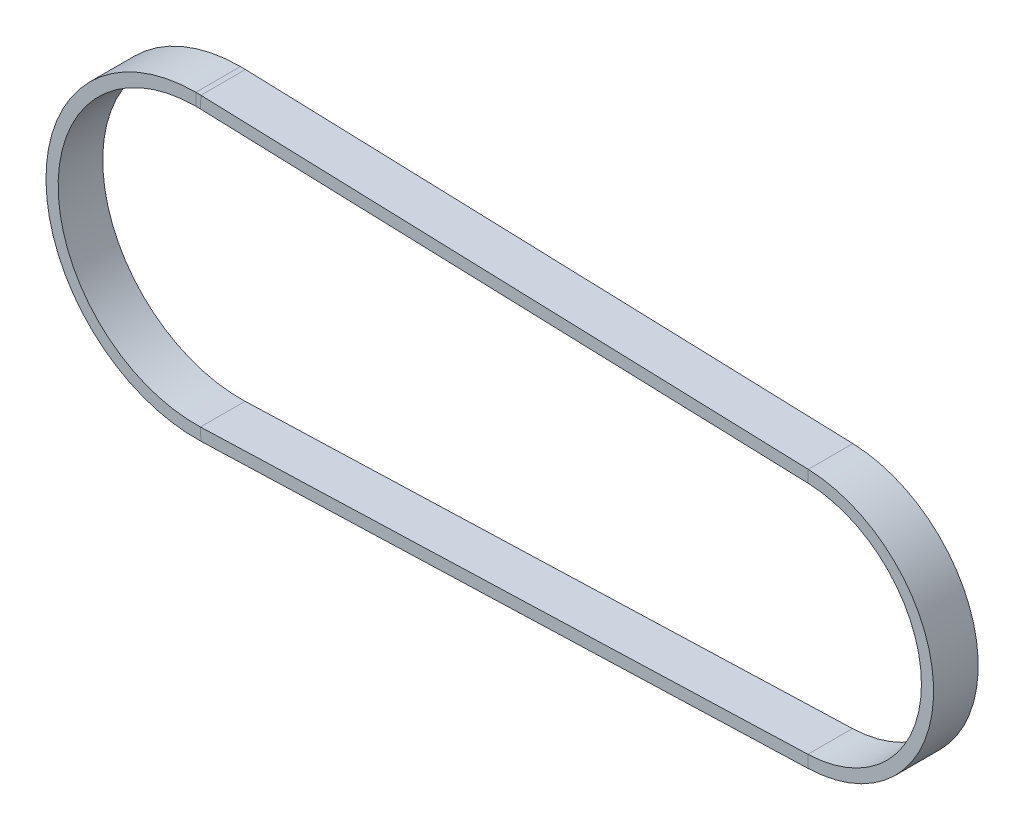
SolidWorks part; units mm, degrees
material "Rubber"
ref_plane "Front Plane" through (0, 0, 0) normal (0, 0, 1) x (1, 0, 0)
ref_plane "Top Plane" through (0, 0, 0) normal (0, 1, 0) x (1, 0, 0)
ref_plane "Right Plane" through (0, 0, 0) normal (1, 0, 0) x (0, 0, -1)
sketch "Sketch1" plane through (0, 0, 0) normal (0, 0, 1) x (1, 0, 0)
  line L0 (1.2333, 36.9794) -> (151.0667, 31.9822)
  line L1 (0, 0) -> (150, 0) construction
  line L2 (1.2333, -36.9794) -> (151.0667, -31.9822)
  arc A0 (1.2333, 36.9794) -> (1.2333, -36.9794) centre (0, 0) ccw
  arc A1 (151.0667, -31.9822) -> (151.0667, 31.9822) centre (150, 0) ccw
  dimension "D1" = 74
  dimension "D2" = 64
  dimension "D3" = 150
sketch "Sketch2" plane through (0, 0, 0) normal (1, 0, 0) x (0, 0, -1)
  line L0 (-5.5, 36.9794) -> (5.5, 36.9794)
  line L2 (-5.5, 36.9794) -> (-5.5, 33.9794)
  line L3 (-5.5, 33.9794) -> (5.5, 33.9794)
  line L4 (5.5, 33.9794) -> (5.5, 36.9794)
  point P3 (0, 36.9794)
  dimension "D1" = 11
  dimension "D2" = 3
sweep "Sweep1" add profiles "Sketch2" path "Sketch1"
